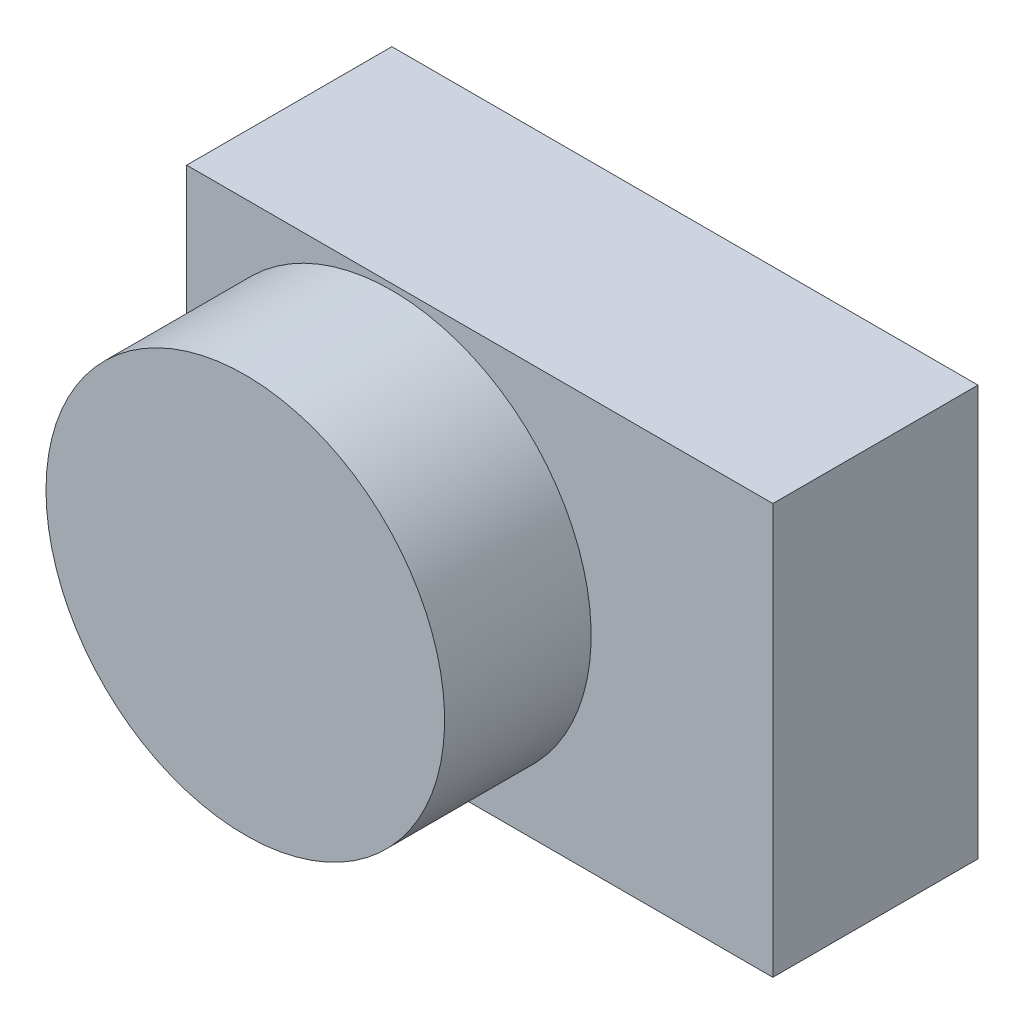
SolidWorks part; units mm, degrees
ref_plane "Спереди" through (0, 0, 0) normal (0, 0, 1) x (1, 0, 0)
ref_plane "Сверху" through (0, 0, 0) normal (0, 1, 0) x (1, 0, 0)
ref_plane "Справа" through (0, 0, 0) normal (1, 0, 0) x (0, 0, -1)
sketch "Эскиз1" plane through (0, 0, 0) normal (0, 0, 1) x (1, 0, 0)
  line L1 (-50, -35) -> (50, -35)
  line L2 (-50, -35) -> (-50, 35)
  line L3 (-50, 35) -> (50, 35)
  line L4 (50, -35) -> (50, 35)
  line L5 (-50, -35) -> (50, 35) construction
  line L6 (-50, 35) -> (50, -35) construction
  circle A0 centre (-15, -1) radius 34
  point P0 (0, 0)
extrude "Бобышка-Вытянуть1" add sketch "Эскиз1" along normal blind 35 contours L3 L4 L1 L2
sketch "Эскиз3" plane through (0, 0, 0) normal (0, 0, -1) x (-1, 0, 0)
  circle A0 centre (15, 0) radius 34
extrude "Бобышка-Вытянуть2" add sketch "Эскиз3" against normal blind 60
ref_point "Точка1"
